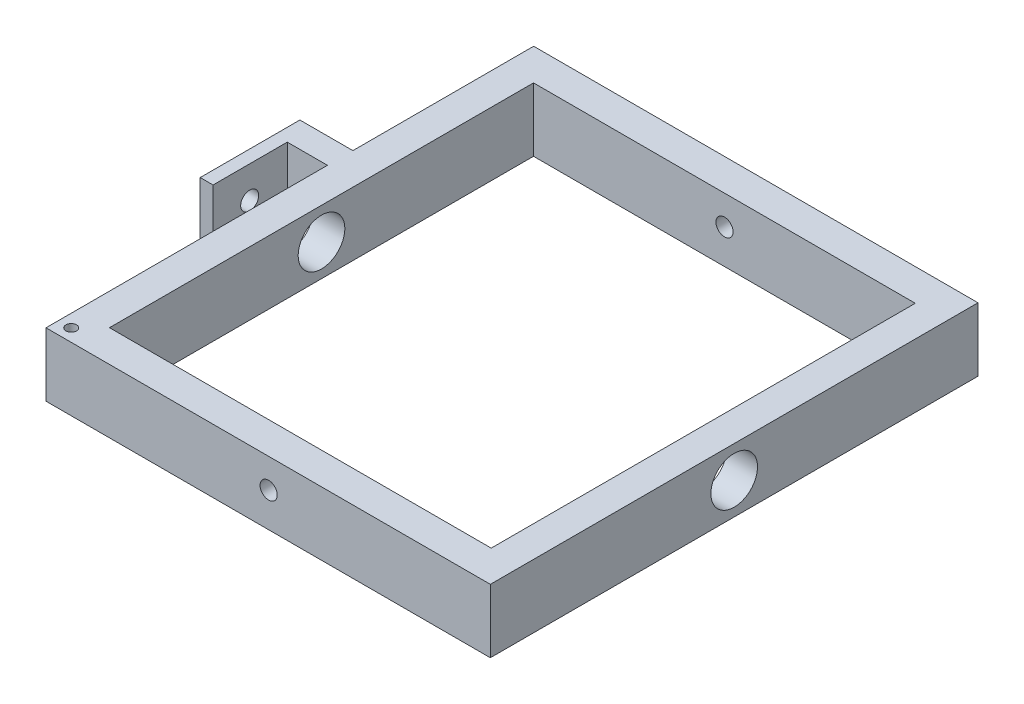
SolidWorks part; units mm, degrees
ref_plane "Front Plane" through (0, 0, 0) normal (0, 0, 1) x (1, 0, 0)
ref_plane "Top Plane" through (0, 0, 0) normal (0, 1, 0) x (1, 0, 0)
ref_plane "Right Plane" through (0, 0, 0) normal (1, 0, 0) x (0, 0, -1)
sketch "Sketch1" plane through (0, 0, 0) normal (0, 1, 0) x (1, 0, 0)
  line L1 (-100, -100) -> (100, -100)
  line L2 (-100, -100) -> (-100, 100)
  line L3 (-100, 100) -> (100, 100)
  line L4 (100, -100) -> (100, 100)
  line L5 (-100, -100) -> (100, 100) construction
  line L6 (-100, 100) -> (100, -100) construction
  line L7 (-115, -115) -> (115, -115)
  line L8 (-115, -115) -> (-115, 115)
  line L9 (-115, 115) -> (115, 115)
  line L10 (115, -115) -> (115, 115)
  line L11 (-115, -115) -> (115, 115) construction
  line L12 (-115, 115) -> (115, -115) construction
  point P0 (0, 0)
  point P6 (0, 0)
extrude "Boss-Extrude1" add sketch "Sketch1" along normal blind 30
sketch "Sketch2" plane through (115, 0, 0) normal (1, 0, 0) x (0, 0, -1)
  circle A0 centre (0, 15) radius 11
extrude "Cut-Extrude3" cut sketch "Sketch2" against normal blind 206
sketch "Sketch3" plane through (115, 0, 0) normal (1, 0, 0) x (0, 0, -1)
  line L0 (-115, 0) -> (115, 0) construction
  line L1 (20.2866, 0) -> (32.935, 0)
  line L2 (20.2866, 0) -> (20.2866, 30)
  line L3 (20.2866, 30) -> (32.935, 30)
  line L4 (32.935, 0) -> (32.935, 30)
  line L5 (-115, 30) -> (115, 30) construction
extrude "Boss-Extrude2" add sketch "Sketch3" along normal blind 28
sketch "Sketch4" plane through (0, 0, -20.2866) normal (0, 0, 1) x (1, 0, 0)
  line L0 (143, 0) -> (115, 0) construction
  line L1 (143, 30) -> (109.723, 30)
  line L2 (143, 30) -> (143, 0)
  line L3 (143, 0) -> (109.723, 0)
  line L4 (109.723, 30) -> (109.723, 0)
extrude "Boss-Extrude4" add sketch "Sketch4" along normal blind 41
sketch "Sketch6" plane through (-115, 0, 0) normal (-1, 0, 0) x (0, 0, 1)
  circle A0 centre (0, 15) radius 4
extrude "Cut-Extrude4" cut sketch "Sketch6" against normal blind 218
sketch "Sketch8" plane through (0, 0, 115) normal (0, 0, 1) x (1, 0, 0)
  circle A0 centre (0, 16.1759) radius 4.0467
extrude "Cut-Extrude6" cut sketch "Sketch8" against normal blind 280
sketch "Sketch9" plane through (-115, 0, 0) normal (-1, 0, 0) x (0, 0, 1)
  circle A0 centre (0, 15) radius 11
extrude "Cut-Extrude7" cut sketch "Sketch9" against normal blind 230
sketch "Sketch11" plane through (0, 0, 20.7134) normal (0, 0, 1) x (1, 0, 0)
  line L0 (115, 0) -> (143, 0) construction
  line L1 (115, 30) -> (134.7762, 30)
  line L2 (115, 30) -> (115, 0)
  line L3 (115, 0) -> (134.7762, 0)
  line L4 (134.7762, 30) -> (134.7762, 0)
extrude "Cut-Extrude8" cut sketch "Sketch11" against normal blind 41
sketch "Sketch12" plane through (-115, 0, 0) normal (-1, 0, 0) x (0, 0, 1)
  circle A0 centre (0, 15) radius 4
extrude "Cut-Extrude9" cut sketch "Sketch12" against normal blind 264
sketch "Sketch13" plane through (0, 30, 0) normal (0, 1, 0) x (1, 0, 0)
  circle A0 centre (106.8511, -106.1772) radius 4
extrude "Cut-Extrude10" cut sketch "Sketch13" against normal blind 264
sketch "Sketch15" plane through (0, 0, 20.7134) normal (0, 0, 1) x (1, 0, 0)
  line L1 (143, 30) -> (134.7762, 30)
  line L2 (143, 30) -> (143, 0)
  line L3 (143, 0) -> (134.7762, 0)
  line L4 (134.7762, 30) -> (134.7762, 0)
extrude "Cut-Extrude11" cut sketch "Sketch15" against normal blind 64
sketch "Sketch16" plane through (0, 0, -20.2866) normal (0, 0, 1) x (1, 0, 0)
  line L0 (115, 0) -> (134.7762, 0) construction
  line L1 (134.7762, 30) -> (128.2637, 30)
  line L2 (134.7762, 30) -> (134.7762, 0)
  line L3 (134.7762, 0) -> (128.2637, 0)
  line L4 (128.2637, 30) -> (128.2637, 0)
extrude "Boss-Extrude5" add sketch "Sketch16" along normal blind 40
sketch "Sketch17" plane through (-115, 0, 0) normal (-1, 0, 0) x (0, 0, 1)
  circle A0 centre (0, 15) radius 4
extrude "Cut-Extrude12" cut sketch "Sketch17" against normal blind 276
sketch "Sketch18" plane through (0, 0, 100) normal (0, 0, -1) x (-1, 0, 0)
  line L0 (100, 0) -> (-100, 0) construction
  line L1 (-100, 30) -> (-89.9715, 30)
  line L2 (-100, 30) -> (-100, 0)
  line L3 (-100, 0) -> (-89.9715, 0)
  line L4 (-89.9715, 30) -> (-89.9715, 0)
extrude "Boss-Extrude6" add sketch "Sketch18" along normal blind 203
sketch "Sketch19" plane through (0, 0, 100) normal (0, 0, -1) x (-1, 0, 0)
  line L0 (100, 0) -> (-89.9715, 0) construction
  line L1 (100, 30) -> (90.08, 30)
  line L2 (100, 30) -> (100, 0)
  line L3 (100, 0) -> (90.08, 0)
  line L4 (90.08, 30) -> (90.08, 0)
extrude "Boss-Extrude7" add sketch "Sketch19" along normal blind 203
sketch "Sketch21" plane through (0, 0, -32.935) normal (0, 0, -1) x (-1, 0, 0)
  line L1 (-115, 0) -> (-134.7762, 0)
  line L2 (-115, 0) -> (-115, 30)
  line L3 (-115, 30) -> (-134.7762, 30)
  line L4 (-134.7762, 0) -> (-134.7762, 30)
extrude "Cut-Extrude13" cut sketch "Sketch21" against normal blind 203
sketch "Sketch22" plane through (0, 0, -115) normal (0, 0, -1) x (-1, 0, 0)
  line L0 (-115, 30) -> (115, 30) construction
  line L1 (-115, 0) -> (-104.559, 0)
  line L2 (-115, 0) -> (-115, 30)
  line L3 (-115, 30) -> (-104.559, 30)
  line L4 (-104.559, 0) -> (-104.559, 30)
extrude "Cut-Extrude14" cut sketch "Sketch22" against normal blind 278
sketch "Sketch23" plane through (0, 30, 0) normal (0, 1, 0) x (1, 0, 0)
  line L1 (104.559, -102.899) -> (100.4969, -102.899)
  line L2 (104.559, -102.899) -> (104.559, -115)
  line L3 (104.559, -115) -> (100.4969, -115)
  line L4 (100.4969, -102.899) -> (100.4969, -115)
extrude "Boss-Extrude8" add sketch "Sketch23" against normal blind 30
sketch "Sketch24" plane through (0, 0, -115) normal (0, 0, -1) x (-1, 0, 0)
  line L0 (-104.559, 0) -> (115, 0) construction
  line L1 (115, 30) -> (105.0104, 30)
  line L2 (115, 30) -> (115, 0)
  line L3 (115, 0) -> (105.0104, 0)
  line L4 (105.0104, 30) -> (105.0104, 0)
extrude "Cut-Extrude15" cut sketch "Sketch24" against normal blind 248
sketch "Sketch25" plane through (-105.0104, 0, 0) normal (-1, 0, 0) x (0, 0, 1)
  circle A0 centre (0, 15) radius 11
extrude "Cut-Extrude16" cut sketch "Sketch25" against normal blind 248
sketch "Sketch26" plane through (-105.0104, 0, 0) normal (-1, 0, 0) x (0, 0, 1)
  line L0 (115, 30) -> (-115, 30) construction
  line L1 (-17.734, 30) -> (-29.7394, 30)
  line L2 (-17.734, 30) -> (-17.734, 0)
  line L3 (-17.734, 0) -> (-29.7394, 0)
  line L4 (-29.7394, 30) -> (-29.7394, 0)
  line L5 (115, 0) -> (-115, 0) construction
extrude "Boss-Extrude9" add sketch "Sketch26" along normal blind 25
sketch "Sketch27" plane through (0, 0, -17.734) normal (0, 0, 1) x (1, 0, 0)
  line L0 (-130.0104, 30) -> (-105.0104, 30) construction
  line L1 (-130.0104, 0) -> (-120.4417, 0)
  line L2 (-130.0104, 0) -> (-130.0104, 30)
  line L3 (-130.0104, 30) -> (-120.4417, 30)
  line L4 (-120.4417, 0) -> (-120.4417, 30)
extrude "Boss-Extrude10" add sketch "Sketch27" along normal blind 35
sketch "Sketch28" plane through (0, 0, 17.266) normal (0, 0, 1) x (1, 0, 0)
  line L0 (-120.4417, 30) -> (-130.0104, 30) construction
  line L1 (-120.4417, 0) -> (-123.9495, 0)
  line L2 (-120.4417, 0) -> (-120.4417, 30)
  line L3 (-120.4417, 30) -> (-123.9495, 30)
  line L4 (-123.9495, 0) -> (-123.9495, 30)
extrude "Cut-Extrude17" cut sketch "Sketch28" against normal blind 35
sketch "Sketch29" plane through (104.559, 0, 0) normal (1, 0, 0) x (0, 0, -1)
  circle A0 centre (0, 15) radius 4.25
extrude "Cut-Extrude18" cut sketch "Sketch29" against normal blind 257
sketch "Sketch33" plane through (0, 0, 0) normal (0, -1, 0) x (-1, 0, 0)
  circle A0 centre (99.0236, -109.0862) radius 2.5
  point P2 (99.0236, -109.0862)
extrude "Cut-Extrude20" cut sketch "Sketch33" against normal blind 44
